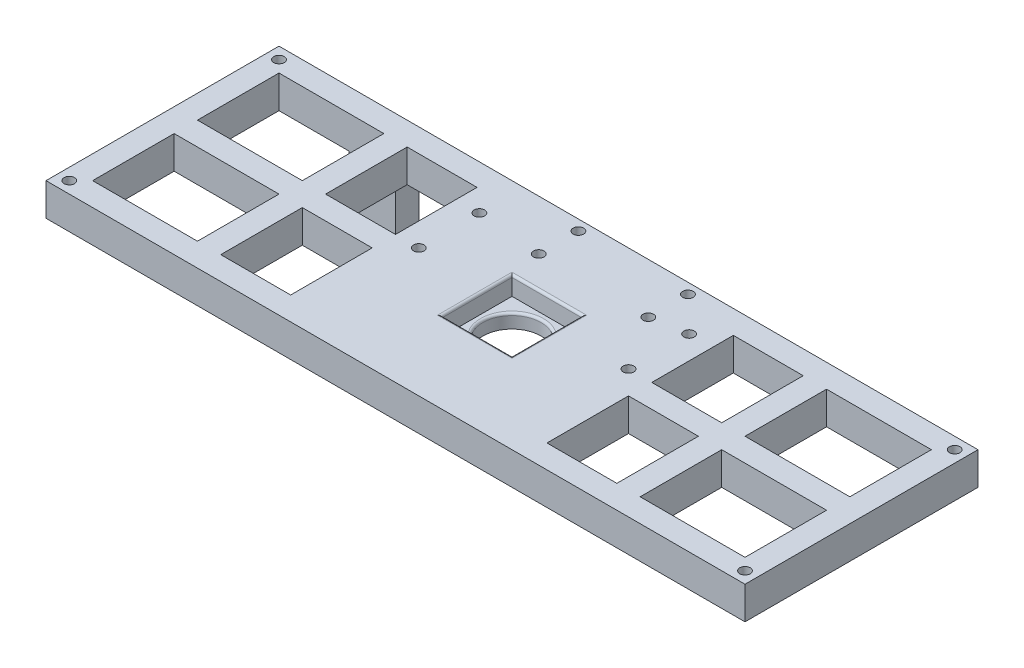
SolidWorks part; units mm, degrees
ref_plane "前视基准面" through (0, 0, 0) normal (0, 0, 1) x (1, 0, 0)
ref_plane "上视基准面" through (0, 0, 0) normal (0, 1, 0) x (1, 0, 0)
ref_plane "右视基准面" through (0, 0, 0) normal (1, 0, 0) x (0, 0, -1)
sketch "草图1" plane through (0, 0, 0) normal (0, 1, 0) x (1, 0, 0)
  line L1 (0, 0) -> (-300, 0)
  line L2 (0, 0) -> (0, 100)
  line L3 (0, 100) -> (-300, 100)
  line L4 (-300, 0) -> (-300, 100)
  dimension "D1" = 300
  dimension "D2" = 100
extrude "凸台-拉伸1" add sketch "草图1" along normal blind 16
sketch "草图2" plane through (0, 16, 0) normal (0, 1, 0) x (1, 0, 0)
  line L0 (-150, 100) -> (-150, 50) construction
  line L1 (0, 100) -> (-300, 100) construction
  line L2 (-300, 50) -> (-150, 50) construction
  line L3 (-300, 100) -> (-300, 0) construction
  line L5 (-165, 65) -> (-135, 65)
  line L6 (-165, 65) -> (-165, 35)
  line L7 (-165, 35) -> (-135, 35)
  line L8 (-135, 65) -> (-135, 35)
  line L9 (-165, 65) -> (-135, 35) construction
  line L10 (-165, 35) -> (-135, 65) construction
  dimension "D1" = 50
  dimension "D2" = 30
  dimension "D3" = 30
extrude "切除-拉伸1" cut sketch "草图2" against normal blind 8
sketch "草图3" plane through (0, 8, 0) normal (0, 1, 0) x (1, 0, 0)
  line L0 (-135, 65) -> (-165, 65) construction
  line L1 (-135, 35) -> (-135, 65) construction
  circle A0 centre (-150, 50) radius 12.5
  dimension "D3" = 25
  dimension "D1" = 15
  dimension "D2" = 15
extrude "切除-拉伸2" cut sketch "草图3" against normal blind 14
sketch "草图4" plane through (0, 16, 0) normal (0, 1, 0) x (1, 0, 0)
  line L0 (-165, 65) -> (-165, 35) construction
  line L1 (-295, 90) -> (-245, 90)
  line L2 (-295, 90) -> (-295, 55)
  line L3 (-295, 55) -> (-245, 55)
  line L4 (-245, 90) -> (-245, 55)
  line L5 (-295, 45) -> (-245, 45)
  line L6 (-295, 45) -> (-295, 10)
  line L7 (-295, 10) -> (-245, 10)
  line L8 (-245, 45) -> (-245, 10)
  line L9 (-235, 90) -> (-185, 90)
  line L10 (-235, 90) -> (-235, 55)
  line L11 (-235, 55) -> (-185, 55)
  line L12 (-185, 90) -> (-185, 55)
  line L13 (-235, 45) -> (-185, 45)
  line L14 (-235, 45) -> (-235, 10)
  line L15 (-235, 10) -> (-185, 10)
  line L16 (-185, 45) -> (-185, 10)
  line L17 (0, 100) -> (-300, 100) construction
  line L18 (-300, 0) -> (0, 0) construction
  line L19 (-300, 100) -> (-300, 0) construction
  line L20 (-150, 100) -> (-150, 73.2626) construction
  line L21 (-5, 10) -> (-55, 10)
  line L22 (-55, 45) -> (-55, 10)
  line L23 (-5, 45) -> (-55, 45)
  line L24 (-5, 45) -> (-5, 10)
  line L25 (-65, 10) -> (-115, 10)
  line L26 (-115, 45) -> (-115, 10)
  line L27 (-65, 45) -> (-115, 45)
  line L28 (-65, 45) -> (-65, 10)
  line L29 (-65, 55) -> (-115, 55)
  line L30 (-115, 90) -> (-115, 55)
  line L31 (-65, 90) -> (-115, 90)
  line L32 (-65, 90) -> (-65, 55)
  line L33 (-5, 55) -> (-55, 55)
  line L34 (-55, 90) -> (-55, 55)
  line L35 (-5, 90) -> (-55, 90)
  line L36 (-5, 90) -> (-5, 55)
  dimension "D1" = 20
  dimension "D2" = 20
  dimension "D3" = 10
  dimension "D4" = 10
  dimension "D5" = 10
  dimension "D6" = 35
  dimension "D7" = 10
  dimension "D8" = 10
  dimension "D9" = 5
  dimension "D10" = 5
  dimension "D11" = 35
  dimension "D12" = 35
  dimension "D13" = 50
  dimension "D14" = 50
  dimension "D15" = 50
  dimension "D16" = 50
extrude "切除-拉伸3" cut sketch "草图4" against normal up to next
sketch "草图7" plane through (-185, 0, 0) normal (-1, 0, 0) x (0, 0, 1)
  line L0 (-45, 0) -> (-10, 0) construction
  line L1 (-10, 0) -> (-10, 16) construction
  line L2 (-10, 16) -> (-45, 16) construction
  line L3 (-45, 16) -> (-45, 0) construction
  line L4 (-90, 0) -> (-55, 0) construction
  line L5 (-55, 0) -> (-55, 16) construction
  line L6 (-55, 16) -> (-90, 16) construction
  line L7 (-90, 16) -> (-90, 0) construction
  line L8 (-45, 0) -> (-10, 0)
  line L9 (-10, 0) -> (-10, 16)
  line L10 (-10, 16) -> (-45, 16)
  line L11 (-45, 16) -> (-45, 0)
  line L12 (-90, 0) -> (-55, 0)
  line L13 (-55, 0) -> (-55, 16)
  line L14 (-55, 16) -> (-90, 16)
  line L15 (-90, 16) -> (-90, 0)
extrude "凸台-拉伸2" add sketch "草图7" along normal blind 20
sketch "草图8" plane through (-115, 0, 0) normal (1, 0, 0) x (0, 0, -1)
  line L0 (10, 0) -> (45, 0) construction
  line L1 (45, 0) -> (45, 16) construction
  line L2 (45, 16) -> (10, 16) construction
  line L3 (10, 16) -> (10, 0) construction
  line L4 (55, 0) -> (90, 0) construction
  line L5 (90, 0) -> (90, 16) construction
  line L6 (90, 16) -> (55, 16) construction
  line L7 (55, 16) -> (55, 0) construction
  line L8 (10, 0) -> (45, 0)
  line L9 (45, 0) -> (45, 16)
  line L10 (45, 16) -> (10, 16)
  line L11 (10, 16) -> (10, 0)
  line L12 (55, 0) -> (90, 0)
  line L13 (90, 0) -> (90, 16)
  line L14 (90, 16) -> (55, 16)
  line L15 (55, 16) -> (55, 0)
extrude "凸台-拉伸3" add sketch "草图8" along normal blind 20
sketch "草图9" plane through (0, 0, 0) normal (0, -1, 0) x (1, 0, 0)
  line L5 (-295, -90) -> (-245, -90) construction
  line L10 (-260, -90) -> (-240, -90)
  line L20 (-260, -90) -> (-260, -100)
  line L21 (-260, -100) -> (-240, -100)
  line L22 (-240, -90) -> (-240, -100)
  line L23 (0, -100) -> (-300, -100) construction
  line L24 (-300, -100) -> (-300, 0) construction
  dimension "D3" = 20
  dimension "D4" = 40
extrude "凸台-拉伸4" add sketch "草图9" along normal blind 25
fillet "圆角1" radius 1 1 edges at (-150, 8, -37.5)
fillet "圆角2" radius 1 4 edges at (-135, 16, -50) (-150, 16, -65) (-150, 16, -35) (-165, 16, -50)
sketch "草图13" plane through (-5, 0, 0) normal (-1, 0, 0) x (0, 0, 1)
  line L0 (-90, 0) -> (-55, 0) construction
  line L1 (-55, 0) -> (-55, 16) construction
  line L2 (-55, 16) -> (-90, 16) construction
  line L3 (-90, 16) -> (-90, 0) construction
  line L4 (-45, 0) -> (-10, 0) construction
  line L5 (-10, 0) -> (-10, 16) construction
  line L6 (-10, 16) -> (-45, 16) construction
  line L7 (-45, 16) -> (-45, 0) construction
  line L8 (-90, 0) -> (-55, 0)
  line L9 (-55, 0) -> (-55, 16)
  line L10 (-55, 16) -> (-90, 16)
  line L11 (-90, 16) -> (-90, 0)
  line L12 (-45, 0) -> (-10, 0)
  line L13 (-10, 0) -> (-10, 16)
  line L14 (-10, 16) -> (-45, 16)
  line L15 (-45, 16) -> (-45, 0)
extrude "凸台-拉伸6" add sketch "草图13" along normal blind 4
sketch "草图14" plane through (-295, 0, 0) normal (1, 0, 0) x (0, 0, -1)
  line L0 (55, 0) -> (90, 0) construction
  line L1 (90, 0) -> (90, 16) construction
  line L2 (90, 16) -> (55, 16) construction
  line L3 (55, 16) -> (55, 0) construction
  line L4 (10, 0) -> (45, 0) construction
  line L5 (45, 0) -> (45, 16) construction
  line L6 (45, 16) -> (10, 16) construction
  line L7 (10, 16) -> (10, 0) construction
  line L8 (55, 0) -> (90, 0)
  line L9 (90, 0) -> (90, 16)
  line L10 (90, 16) -> (55, 16)
  line L11 (55, 16) -> (55, 0)
  line L12 (10, 0) -> (45, 0)
  line L13 (45, 0) -> (45, 16)
  line L14 (45, 16) -> (10, 16)
  line L15 (10, 16) -> (10, 0)
extrude "凸台-拉伸7" add sketch "草图14" along normal blind 4
sketch "草图17" plane through (-291, 0, 0) normal (1, 0, 0) x (0, 0, -1)
  line L0 (10, 16) -> (10, 0) construction
  line L1 (10, 0) -> (45, 0) construction
  line L2 (45, 0) -> (45, 16) construction
  line L3 (45, 16) -> (10, 16) construction
  line L4 (55, 16) -> (55, 0) construction
  line L5 (55, 0) -> (90, 0) construction
  line L6 (90, 0) -> (90, 16) construction
  line L7 (90, 16) -> (55, 16) construction
  line L8 (10, 16) -> (10, 0)
  line L9 (10, 0) -> (45, 0)
  line L10 (45, 0) -> (45, 16)
  line L11 (45, 16) -> (10, 16)
  line L12 (55, 16) -> (55, 0)
  line L13 (55, 0) -> (90, 0)
  line L14 (90, 0) -> (90, 16)
  line L15 (90, 16) -> (55, 16)
extrude "凸台-拉伸8" add sketch "草图17" along normal blind 1
sketch "草图18" plane through (-9, 0, 0) normal (-1, 0, 0) x (0, 0, 1)
  line L0 (-45, 16) -> (-45, 0) construction
  line L1 (-45, 0) -> (-10, 0) construction
  line L2 (-10, 0) -> (-10, 16) construction
  line L3 (-10, 16) -> (-45, 16) construction
  line L4 (-90, 16) -> (-90, 0) construction
  line L5 (-90, 0) -> (-55, 0) construction
  line L6 (-55, 0) -> (-55, 16) construction
  line L7 (-55, 16) -> (-90, 16) construction
  line L8 (-45, 16) -> (-45, 0)
  line L9 (-45, 0) -> (-10, 0)
  line L10 (-10, 0) -> (-10, 16)
  line L11 (-10, 16) -> (-45, 16)
  line L12 (-90, 16) -> (-90, 0)
  line L13 (-90, 0) -> (-55, 0)
  line L14 (-55, 0) -> (-55, 16)
  line L15 (-55, 16) -> (-90, 16)
extrude "凸台-拉伸9" add sketch "草图18" along normal blind 1
sketch "草图19" plane through (0, 16, 0) normal (0, 1, 0) x (1, 0, 0)
  line L0 (-300, 100) -> (-295, 100) construction
  line L1 (0, 100) -> (-300, 100) construction
  line L2 (-295, 100) -> (-295, 95) construction
  line L3 (-150, 100) -> (-150, 83.4567) construction
  line L4 (-300, 50) -> (-202.8605, 50) construction
  line L5 (-300, 100) -> (-300, 0) construction
  line L6 (-150, 0) -> (-150, 22.48) construction
  line L7 (-300, 0) -> (0, 0) construction
  line L8 (-5, 100) -> (-5, 95) construction
  line L9 (0, 100) -> (-5, 100) construction
  circle A0 centre (-295, 95) radius 2.25
  circle A1 centre (-295, 5) radius 2.25
  circle A4 centre (-5, 5) radius 2.25
  circle A5 centre (-5, 95) radius 2.25
  dimension "D3" = 4.5
  dimension "D1" = 5
  dimension "D2" = 5
extrude "切除-拉伸8" cut sketch "草图19" against normal blind 5
sketch "草图20" plane through (0, 0, 0) normal (0, -1, 0) x (1, 0, 0)
  circle A2 centre (-295, -95) radius 2.25 construction
  circle A3 centre (-295, -5) radius 2.25 construction
  circle A6 centre (-295, -95) radius 2.25
  circle A7 centre (-295, -5) radius 2.25
  circle A8 centre (-5, -95) radius 2.25 construction
  circle A9 centre (-5, -5) radius 2.25 construction
  circle A10 centre (-5, -95) radius 2.25
  circle A11 centre (-5, -5) radius 2.25
extrude "切除-拉伸9" cut sketch "草图20" against normal blind 7
sketch "草图24" [suppressed] plane through (0, 16, 0) normal (0, 1, 0) x (1, 0, 0)
  circle A0 centre (-195, 81) radius 2.25
  circle A1 centre (-205, 54.9815) radius 2.25
  circle A2 centre (-105, 81) radius 2.25
  circle A3 centre (-115, 54.9815) radius 2.25
  dimension "D1" = 4.5
  dimension "D2" = 4.5
  dimension "D3" = 4.5
  dimension "D4" = 4.5
extrude "切除-拉伸13" [suppressed] cut sketch "草图24" against normal blind 5
sketch "草图26" plane through (0, 0, 0) normal (0, -1, 0) x (1, 0, 0)
  line L12 (-260, -90) -> (-290, -90)
  line L13 (-290, -90) -> (-290, -55)
  line L14 (-290, -55) -> (-245, -55)
  line L15 (-245, -55) -> (-245, -90)
  line L16 (-245, -90) -> (-240, -90)
  line L17 (-240, -90) -> (-240, -100)
  line L18 (-240, -100) -> (0, -100)
  line L19 (0, -100) -> (0, 0)
  line L20 (0, 0) -> (-300, 0)
  line L21 (-300, 0) -> (-300, -100)
  line L22 (-300, -100) -> (-260, -100)
  line L23 (-260, -100) -> (-260, -90)
  line L24 (-260, -90) -> (-290, -90)
  line L25 (-290, -90) -> (-290, -55)
  line L26 (-290, -55) -> (-245, -55)
  line L27 (-245, -55) -> (-245, -90)
  line L28 (-245, -90) -> (-240, -90)
  line L29 (-240, -90) -> (-240, -100)
  line L30 (-240, -100) -> (0, -100)
  line L31 (0, -100) -> (0, 0)
  line L32 (0, 0) -> (-300, 0)
  line L33 (-300, 0) -> (-300, -100)
  line L34 (-300, -100) -> (-260, -100)
  line L35 (-260, -100) -> (-260, -90)
  dimension "D1" = 0
extrude "切除-拉伸15" cut sketch "草图26" against normal blind 2
sketch "草图28" plane through (0, 16, 0) normal (0, 1, 0) x (1, 0, 0)
  line L0 (-205, 55) -> (-205, 90) construction
  line L1 (0, 100) -> (-300, 100) construction
  line L2 (-95, 90) -> (-95, 55) construction
  circle A8 centre (-105.0028, 55) radius 2.25
  circle A9 centre (-105, 81) radius 2.25
  circle A10 centre (-120, 78.5) radius 2.25
  circle A11 centre (-120, 95.5) radius 2.25
  circle A12 centre (-167.0001, 78.5) radius 2.25
  circle A13 centre (-167.0001, 95.5) radius 2.25
  circle A14 centre (-195, 55) radius 2.25
  circle A15 centre (-195, 81) radius 2.25
  dimension "D1" = 10
  dimension "D2" = 10
  dimension "D3" = 26
  dimension "D4" = 19
  dimension "D5" = 4.5
  dimension "D6" = 4.5
  dimension "D7" = 17
  dimension "D8" = 4.5
  dimension "D9" = 4.5
  dimension "D10" = 17
  dimension "D11" = 47.0001
  dimension "D12" = 47.0001
  dimension "D13" = 4.5
  dimension "D14" = 4.5
  dimension "D15" = 4.5
  dimension "D16" = 4.5
  dimension "D17" = 25
  dimension "D18" = 25
  dimension "D19" = 10
  dimension "D20" = 10.0028
  dimension "D21" = 26
  dimension "D22" = 19
  dimension "D23" = 4.5
  dimension "D24" = 4.5
extrude "切除-拉伸18" cut sketch "草图28" against normal blind 5
sketch "草图30" plane through (0, 11, 0) normal (0, 1, 0) x (1, 0, 0)
  circle A2 centre (-195, 81) radius 1.5
  circle A3 centre (-195, 55) radius 1.5
  circle A4 centre (-167.0001, 95.5) radius 1.5
  circle A5 centre (-167.0001, 78.5) radius 1.5
  circle A6 centre (-120, 95.5) radius 1.5
  circle A7 centre (-120, 78.5) radius 1.5
  circle A8 centre (-105, 81) radius 1.5
  circle A9 centre (-105.0028, 55) radius 1.5
  dimension "D1" = 3
extrude "切除-拉伸20" cut sketch "草图30" against normal blind 4
